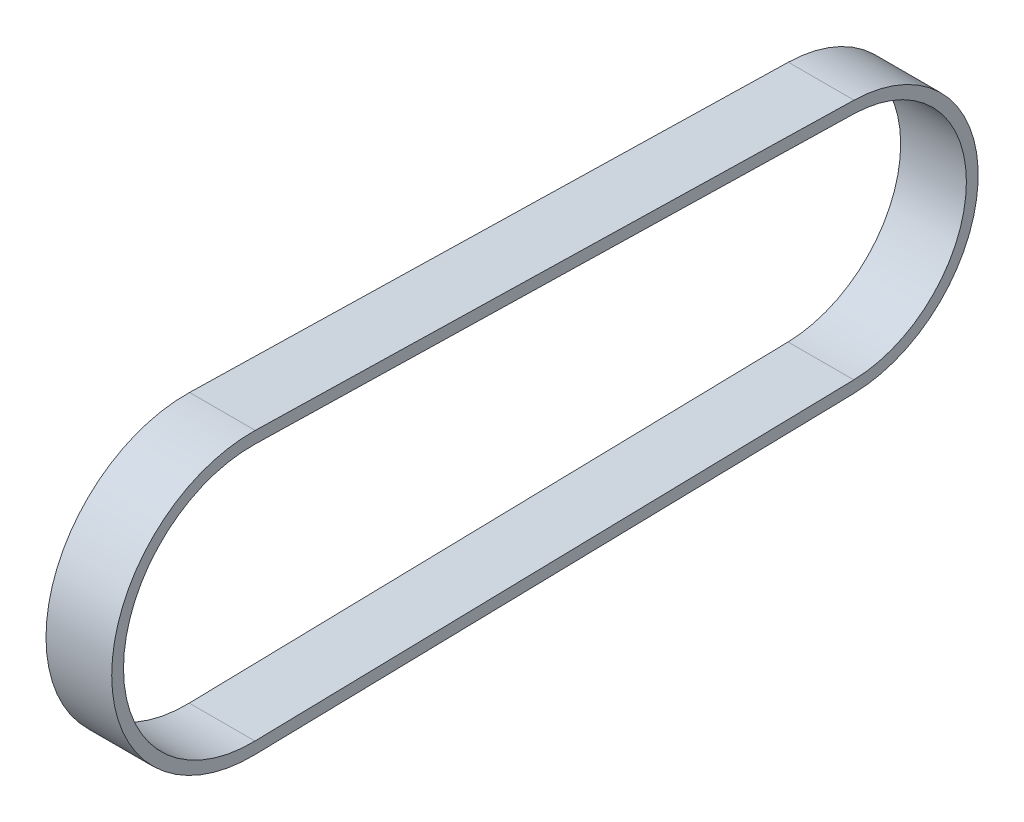
SolidWorks part; units mm, degrees
material "Rubber"
ref_plane "Front Plane" through (0, 0, 0) normal (0, 0, 1) x (1, 0, 0)
ref_plane "Top Plane" through (0, 0, 0) normal (0, 1, 0) x (1, 0, 0)
ref_plane "Right Plane" through (0, 0, 0) normal (1, 0, 0) x (0, 0, -1)
sketch "Sketch1" plane through (0, 0, 0) normal (1, 0, 0) x (0, 0, -1)
  line L0 (0.289, 12.9329) -> (58.1577, 11.6396) construction
  line L1 (58.1577, -11.6396) -> (0.289, -12.9329) construction
  line L6 (0.3031, 13.5627) -> (58.1718, 12.2694)
  line L7 (58.1718, -12.2694) -> (0.3031, -13.5627)
  line L8 (0.2776, 12.423) -> (58.1463, 11.1297)
  line L9 (58.1463, -11.1297) -> (0.2776, -12.423)
  line L10 (0, 0) -> (57.8975, 0) construction
  circle A1 centre (57.8975, 0) radius 11.6425 construction
  arc A2 (58.1577, 11.6396) -> (58.1577, -11.6396) centre (57.8975, 0) cw construction
  arc A3 (0.289, -12.9329) -> (0.289, 12.9329) centre (0, 0) cw construction
  arc A8 (58.1718, 12.2694) -> (58.1718, -12.2694) centre (57.8975, 0) cw
  arc A9 (0.3031, -13.5627) -> (0.3031, 13.5627) centre (0, 0) cw
  arc A10 (58.1463, 11.1297) -> (58.1463, -11.1297) centre (57.8975, 0) cw
  arc A11 (0.2776, -12.423) -> (0.2776, 12.423) centre (0, 0) cw
  circle A12 centre (0, 0) radius 12.9361 construction
  dimension "D2" = 23.285
  dimension "D6" = 25.8722
  dimension "D4" = 1.14
  dimension "D3" = 57.8975
  dimension "D5" = 0.51
extrude "Boss-Extrude1" add sketch "Sketch1" along normal blind 6.35
equation "\"D2@Sketch1\"=.08*36/pi"
equation "\"D1@Sketch1\"=.08*95"
equation "\"D6@Sketch1\"=40*.08/pi"
